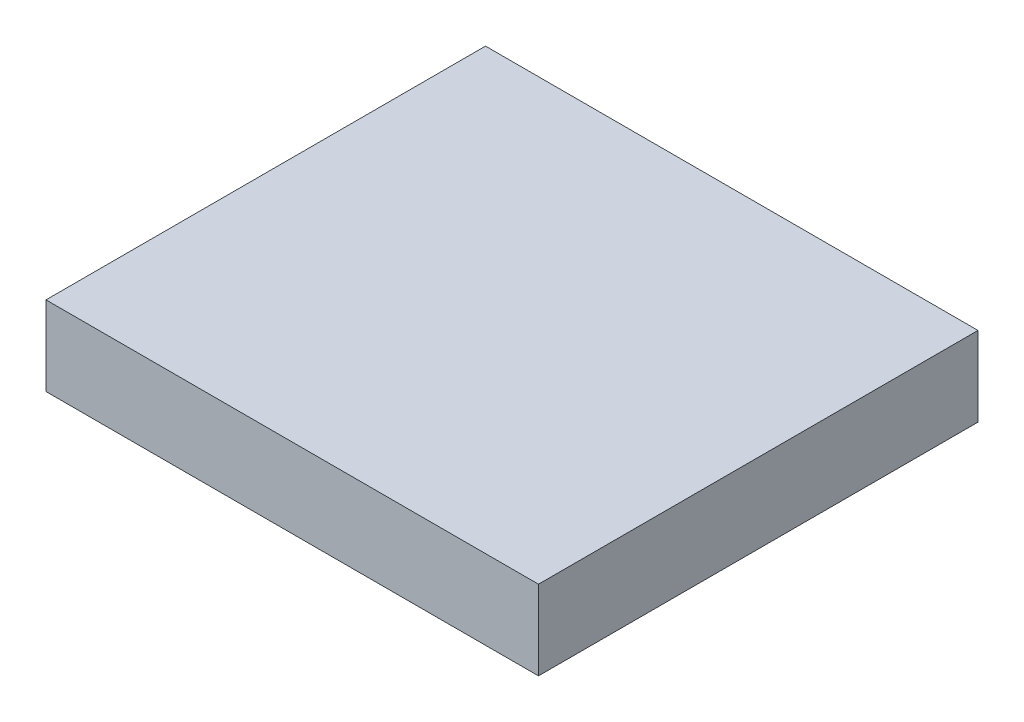
SolidWorks part; units mm, degrees
ref_plane "Front Plane" through (0, 0, 0) normal (0, 0, 1) x (1, 0, 0)
ref_plane "Top Plane" through (0, 0, 0) normal (0, 1, 0) x (1, 0, 0)
ref_plane "Right Plane" through (0, 0, 0) normal (1, 0, 0) x (0, 0, -1)
sketch "Sketch2" plane through (0, 0, 0) normal (0, 1, 0) x (1, 0, 0)
  line L1 (-46.5, 41.5) -> (46.5, 41.5)
  line L2 (-46.5, 41.5) -> (-46.5, -41.5)
  line L3 (-46.5, -41.5) -> (46.5, -41.5)
  line L4 (46.5, 41.5) -> (46.5, -41.5)
  line L5 (-46.5, 41.5) -> (46.5, -41.5) construction
  line L6 (-46.5, -41.5) -> (46.5, 41.5) construction
  point P0 (0, 0)
  dimension "D1" = 93
  dimension "D2" = 83
extrude "Boss-Extrude1" add sketch "Sketch2" along normal blind 15
